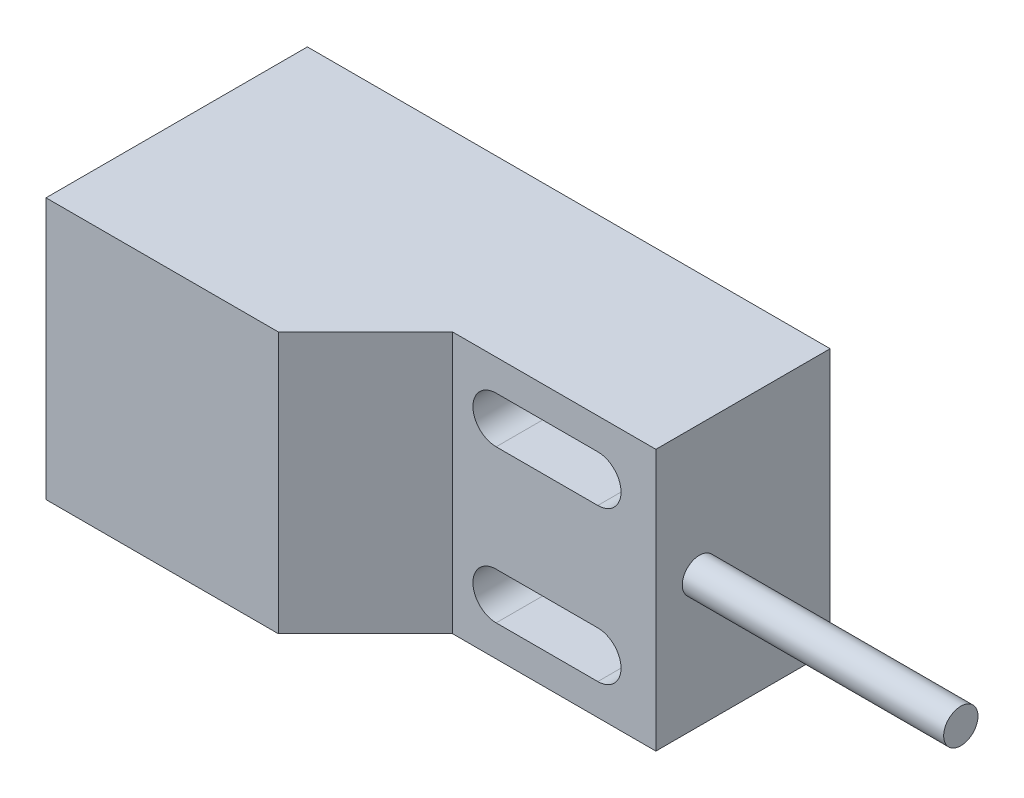
SolidWorks part; units mm, degrees
ref_plane "Płaszczyzna przednia" through (0, 0, 0) normal (0, 0, 1) x (1, 0, 0)
ref_plane "Płaszczyzna górna" through (0, 0, 0) normal (0, 1, 0) x (1, 0, 0)
ref_plane "Płaszczyzna prawa" through (0, 0, 0) normal (1, 0, 0) x (0, 0, -1)
sketch "Szkic1" plane through (0, 0, 0) normal (0, 0, 1) x (1, 0, 0)
  line L1 (-18, 9) -> (18, 9)
  line L2 (-18, 9) -> (-18, -9)
  line L3 (-18, -9) -> (18, -9)
  line L4 (18, 9) -> (18, -9)
  line L5 (-18, 9) -> (18, -9) construction
  line L6 (-18, -9) -> (18, 9) construction
  point P0 (0, 0)
  dimension "D1" = 18
  dimension "D2" = 36
extrude "Dodanie-wyciągnięcie1" add sketch "Szkic1" along normal mid plane 18
sketch "Szkic2" plane through (0, -9, 0) normal (0, -1, 0) x (1, 0, 0)
  line L0 (-2, 9) -> (4, 3)
  line L1 (-18, 9) -> (18, 9) construction
  line L2 (4, 3) -> (18, 3)
  line L3 (18, 9) -> (18, -9) construction
  line L4 (18, 3) -> (18, 9)
  line L5 (18, 9) -> (-2, 9)
  line L6 (-18, -9) -> (18, -9) construction
  line L7 (-18, 9) -> (-18, -9) construction
  dimension "D1" = 12
  dimension "D2" = 16
  dimension "D3" = 45
extrude "Wytnij-wyciągnięcie1" cut sketch "Szkic2" against normal blind 18
sketch "Szkic3" plane through (18, 0, 0) normal (1, 0, 0) x (0, 0, -1)
  circle A0 centre (0, 0) radius 1.1826
extrude "Dodanie-wyciągnięcie2" add sketch "Szkic3" along normal blind 18
sketch "Szkic4" plane through (0, 0, 3) normal (0, 0, 1) x (1, 0, 0)
  line L0 (7, 5.25) -> (14, 5.25) construction
  line L1 (7, 6.85) -> (14, 6.85)
  line L2 (7, 3.65) -> (14, 3.65)
  line L3 (0, 0) -> (50000, 0) construction
  line L4 (7, -5.25) -> (14, -5.25) construction
  line L5 (7, -6.85) -> (14, -6.85)
  line L6 (7, -3.65) -> (14, -3.65)
  line L7 (-18, 9) -> (-18, -9) construction
  arc A0 (7, 6.85) -> (7, 3.65) centre (7, 5.25) ccw
  arc A1 (14, 3.65) -> (14, 6.85) centre (14, 5.25) ccw
  arc A2 (7, -6.85) -> (7, -3.65) centre (7, -5.25) cw
  arc A3 (14, -3.65) -> (14, -6.85) centre (14, -5.25) cw
  point P2 (10.5, 5.25)
  point P12 (10.5, -5.25)
  dimension "D2" = 7
  dimension "D1" = 3.2
  dimension "D3" = 10.5
  dimension "D4" = 28.5
extrude "Wytnij-wyciągnięcie2" cut sketch "Szkic4" against normal through all
